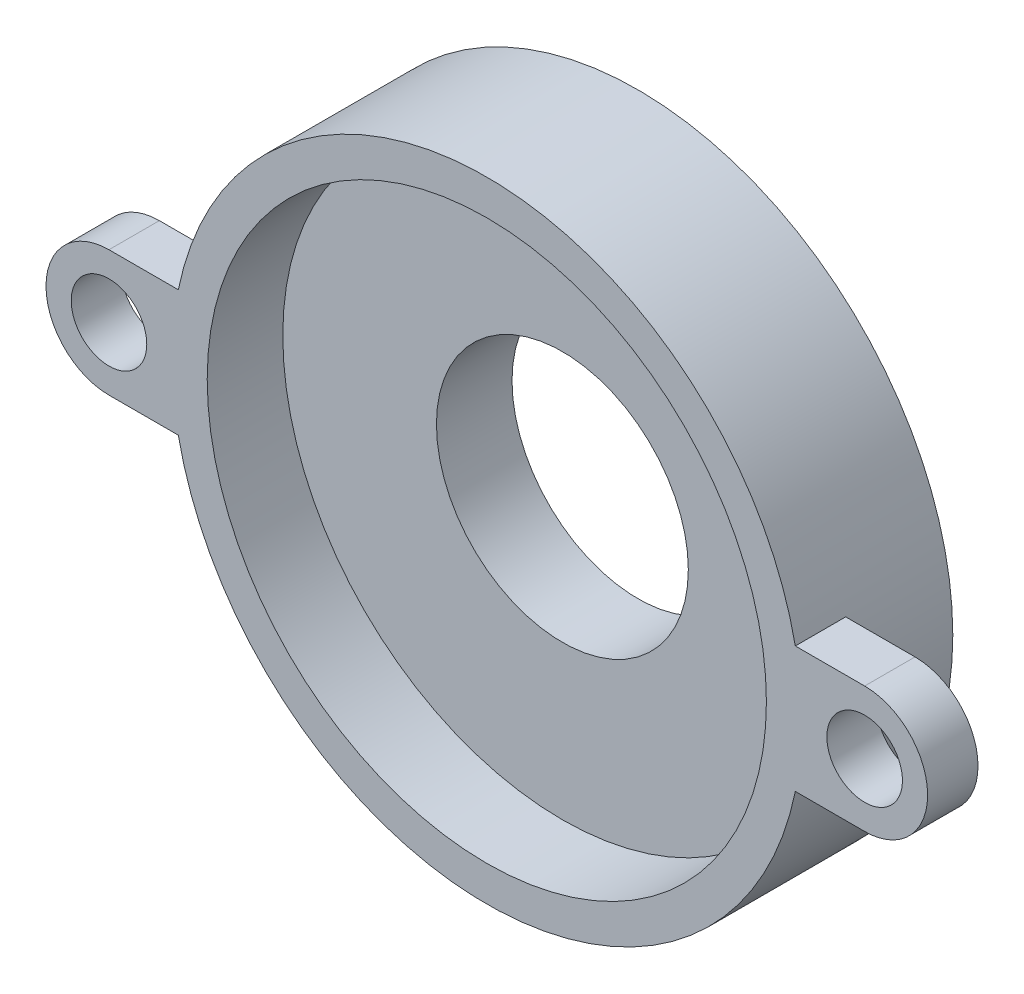
SolidWorks part; units mm, degrees
ref_plane "Front Plane" through (0, 0, 0) normal (0, 0, 1) x (1, 0, 0)
ref_plane "Top Plane" through (0, 0, 0) normal (0, 1, 0) x (1, 0, 0)
ref_plane "Right Plane" through (0, 0, 0) normal (1, 0, 0) x (0, 0, -1)
sketch "Sketch2" plane through (0, 0, 0) normal (0, 0, 1) x (1, 0, 0)
  circle A0 centre (0, 0) radius 12.5
  circle A1 centre (0, 0) radius 5
  dimension "D1" = 25
  dimension "D2" = 10
extrude "Boss-Extrude3" add sketch "Sketch2" along normal blind 6
sketch "Sketch4" plane through (0, 0, 6) normal (0, 0, 1) x (1, 0, 0)
  circle A0 centre (0, 0) radius 11.1
  dimension "D1" = 22.2
extrude "Cut-Extrude1" cut sketch "Sketch4" against normal blind 3
sketch "Sketch5" plane through (0, 0, 6) normal (0, 0, 1) x (1, 0, 0)
  line L0 (-15, 2.5) -> (-12.2474, 2.5)
  line L1 (-15, -2.5) -> (-12.2474, -2.5)
  line L2 (0, 14.6095) -> (0, -13.9164) construction
  line L3 (15, -2.5) -> (12.2474, -2.5)
  line L4 (15, 2.5) -> (12.2474, 2.5)
  circle A0 centre (-15, 0) radius 1.5
  arc A1 (-15, 2.5) -> (-15, -2.5) centre (-15, 0) ccw
  circle A2 centre (0, 0) radius 12.5 construction
  arc A3 (-12.2474, 2.5) -> (-12.2474, -2.5) centre (0, 0) ccw
  arc A4 (12.2474, 2.5) -> (12.2474, -2.5) centre (0, 0) cw
  arc A5 (15, 2.5) -> (15, -2.5) centre (15, 0) cw
  circle A6 centre (15, 0) radius 1.5
  dimension "D1" = 3
  dimension "D2" = 5
  dimension "D3" = 15
extrude "Boss-Extrude4" add sketch "Sketch5" against normal blind 2
